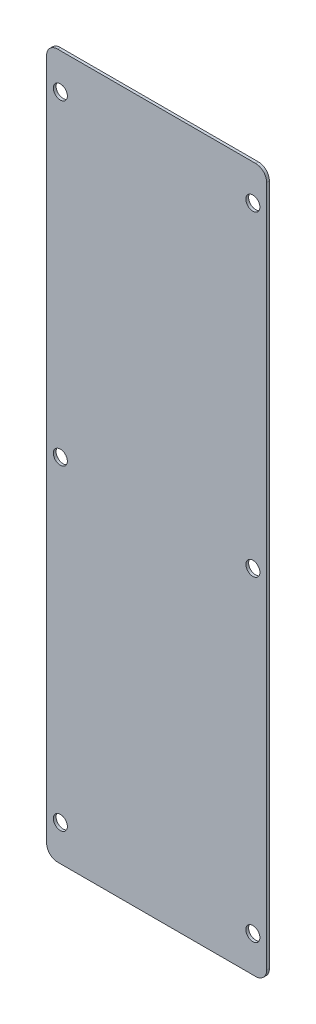
SolidWorks part; units mm, degrees
material "AISI 304"
ref_plane "Front Plane" through (0, 0, 0) normal (0, 0, 1) x (1, 0, 0)
ref_plane "Top Plane" through (0, 0, 0) normal (0, 1, 0) x (1, 0, 0)
ref_plane "Right Plane" through (0, 0, 0) normal (1, 0, 0) x (0, 0, -1)
sketch "Sketch1" plane through (0, 0, 0) normal (0, 0, 1) x (1, 0, 0)
  line L1 (-40, -128) -> (40, -128)
  line L2 (-40, -128) -> (-40, 128)
  line L3 (-40, 128) -> (40, 128)
  line L4 (40, -128) -> (40, 128)
  line L5 (-40, -128) -> (40, 128) construction
  line L6 (-40, 128) -> (40, -128) construction
  point P0 (0, 0)
  dimension "D1" = 80
  dimension "D2" = 256
extrude "Boss-Extrude1" add sketch "Sketch1" along normal blind 1
fillet "Fillet1" radius 4 4 edges at (-40, 128, 0.5) (-40, -128, 0.5) (40, -128, 0.5) (40, 128, 0.5)
sketch "Sketch2" plane through (0, 0, 1) normal (0, 0, 1) x (1, 0, 0)
  circle A0 centre (35, -115) radius 2.55
  circle A2 centre (-35, -115) radius 2.55
  circle A3 centre (-35, 0) radius 2.55
  circle A4 centre (35, 0) radius 2.55
  circle A5 centre (35, 115) radius 2.55
  circle A6 centre (-35, 115) radius 2.55
  dimension "D1" = 5.1
extrude "Cut-Extrude1" cut sketch "Sketch2" against normal through all
equation "\"Base-Width\"= 420"
equation "\"Base-Height\"= 320"
equation "\"Support-Rod-Diameter\"= 16"
equation "\"Support-Rod-X-Offset\"= 35"
equation "\"Support-Rod-Y-Offset\"= 35"
equation "\"Base-Thickness\"= 5"
equation "\"Base-Depth\"= 82"
equation "\"Corner-Radius-Major\"= \"Support-Rod-Diameter\""
equation "\"Cutout-Horizontal\"= \"Base-Width\" * 0.8"
equation "\"Cutout-Vertical\"= \"Base-Height\" * 0.6"
equation "\"Outer-Support-Bore-Diameter\"= 6.1"
equation "\"Inner-Support-Bore-Diameter\"= 8.2"
equation "\"Cutout-Depth\"= 20"
equation "\"D1@Sketch1\"=\"Base-Depth\" - 2"
equation "\"D2@Sketch1\"= \"Base-Height\" - ( \"Support-Rod-Diameter\" * 4 )"
equation "\"D2@Sketch1\"=\"Base-Width\""
equation "\"D1@Sketch7\"=\"Cutout-Vertical\""
equation "\"D2@Sketch6\"=\"Cutout-Horizontal\""
equation "\"D2@Sketch8\"= \"Base-Width\" - ( \"Support-Rod-X-Offset\" ) + 5"
equation "\"D1@Sketch8\" = \"Base-Height\" - \"Support-Rod-Y-Offset\" + 10"
equation "\"D1@Major-Fillet\" = \"Corner-Radius-Major\""
equation "\"D1@Sketch1\"=\"Base-Height\""
